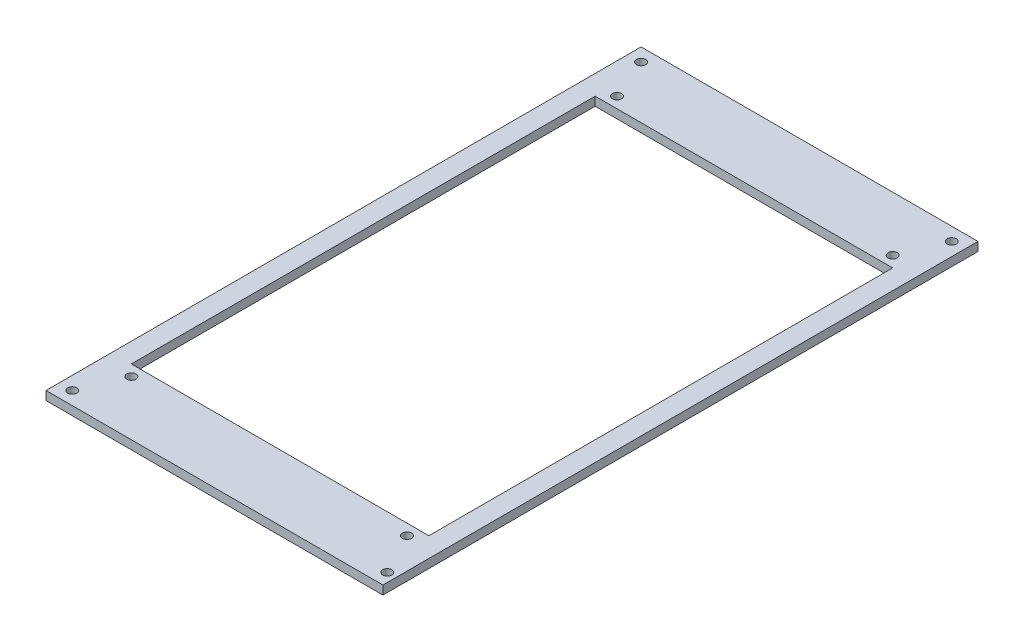
SolidWorks part; units mm, degrees
ref_plane "前视基准面" through (0, 0, 0) normal (0, 0, 1) x (1, 0, 0)
ref_plane "上视基准面" through (0, 0, 0) normal (0, 1, 0) x (1, 0, 0)
ref_plane "右视基准面" through (0, 0, 0) normal (1, 0, 0) x (0, 0, -1)
sketch "草图2" plane through (0, 0, 0) normal (0, 1, 0) x (1, 0, 0)
  line L0 (0, 0) -> (77, -136) construction
  line L1 (0, 0) -> (77, 0)
  line L2 (0, 0) -> (0, -136)
  line L3 (0, -136) -> (77, -136)
  line L4 (77, 0) -> (77, -136)
  line L5 (77, 0) -> (0, -136) construction
  line L6 (0, -3) -> (77, -3) construction
  line L7 (4.5, -15) -> (72.5, -15)
  line L8 (4.5, -15) -> (4.5, -121)
  line L9 (4.5, -121) -> (72.5, -121)
  line L10 (72.5, -15) -> (72.5, -121)
  line L11 (4.5, -15) -> (72.5, -121) construction
  line L12 (4.5, -121) -> (72.5, -15) construction
  line L13 (0, -133) -> (77, -133) construction
  line L14 (3, 0) -> (3, -136) construction
  line L15 (74, 0) -> (74, -136) construction
  line L25 (7, -12.5) -> (70, -12.5) construction
  line L26 (7, -12.5) -> (7, -123.5) construction
  line L27 (7, -123.5) -> (70, -123.5) construction
  line L28 (70, -12.5) -> (70, -123.5) construction
  line L29 (7, -12.5) -> (70, -123.5) construction
  line L30 (7, -123.5) -> (70, -12.5) construction
  circle A0 centre (3, -3) radius 1.05
  circle A1 centre (74, -3) radius 1.05
  circle A2 centre (3, -133) radius 1.05
  circle A3 centre (75, -133) radius 1.05
  circle A4 centre (7, -12.5) radius 1.05
  circle A5 centre (70, -12.5) radius 1.05
  circle A6 centre (70, -123.5) radius 1.05
  circle A7 centre (7, -123.5) radius 1.05
  point P5 (38.5, -68)
  point P26 (38.5, -68)
  point P35 (0, 0)
  dimension "D9" = 2.1
  dimension "D10" = 2.1
  dimension "D11" = 2.1
  dimension "D12" = 2.1
  dimension "D15" = 2.1
  dimension "D16" = 2.1
  dimension "D17" = 2.1
  dimension "D18" = 2.1
  dimension "D1" = 136
  dimension "D2" = 77
  dimension "D3" = 106
  dimension "D4" = 68
  dimension "D5" = 3
  dimension "D6" = 3
  dimension "D7" = 3
  dimension "D8" = 3
  dimension "D13" = 63
  dimension "D14" = 111
  dimension "D19" = 2
extrude "凸台-拉伸1" add sketch "草图2" along normal blind 2
